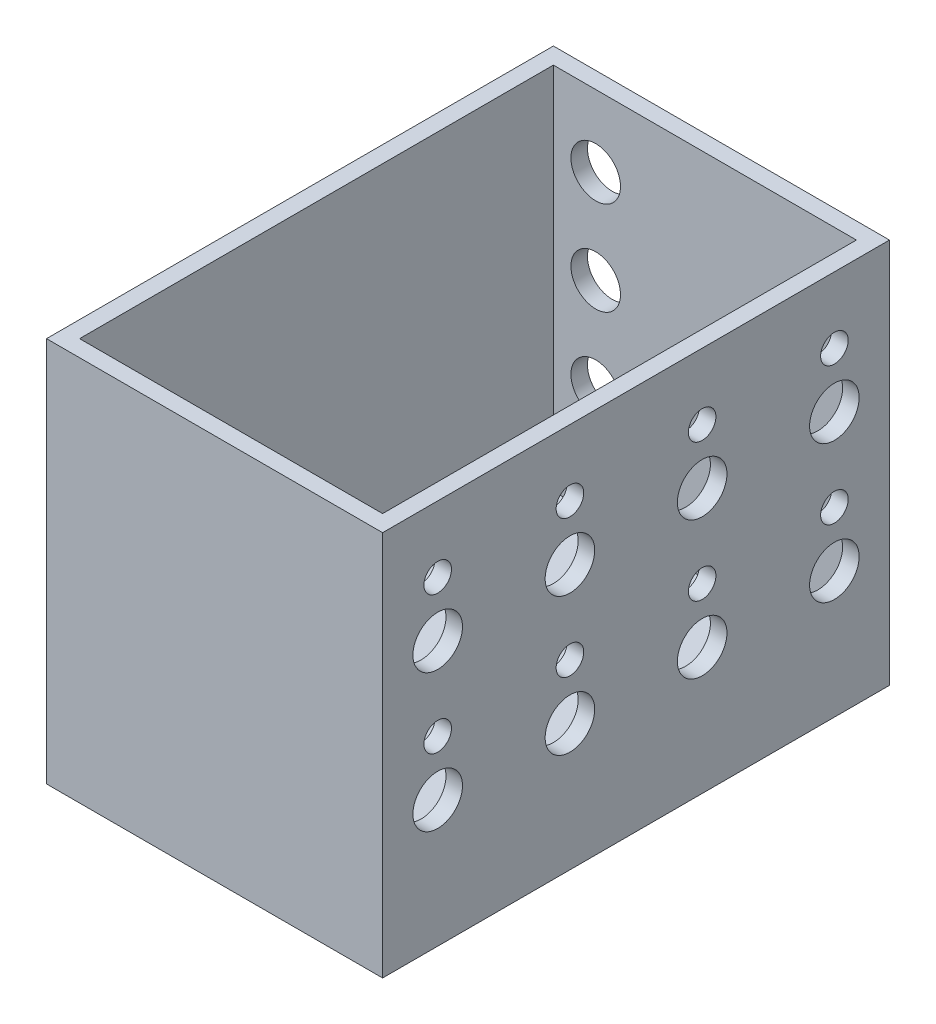
SolidWorks part; units mm, degrees
ref_plane "Front Plane" through (0, 0, 0) normal (0, 0, 1) x (1, 0, 0)
ref_plane "Top Plane" through (0, 0, 0) normal (0, 1, 0) x (1, 0, 0)
ref_plane "Right Plane" through (0, 0, 0) normal (1, 0, 0) x (0, 0, -1)
sketch "Sketch1" plane through (0, 0, 0) normal (0, 1, 0) x (1, 0, 0)
  line L1 (-27.5, -43) -> (27.5, -43)
  line L2 (-27.5, -43) -> (-27.5, 43)
  line L3 (-27.5, 43) -> (27.5, 43)
  line L4 (27.5, -43) -> (27.5, 43)
  line L5 (-27.5, -43) -> (27.5, 43) construction
  line L6 (-27.5, 43) -> (27.5, -43) construction
  point P0 (0, 0)
  dimension "D1" = 86
  dimension "D2" = 55
extrude "Boss-Extrude1" add sketch "Sketch1" along normal blind 3
sketch "Sketch2" plane through (0, 3, 0) normal (0, 1, 0) x (1, 0, 0)
  line L1 (-22.5, -22.5) -> (22.5, -22.5)
  line L2 (-22.5, -22.5) -> (-22.5, 22.5)
  line L3 (-22.5, 22.5) -> (22.5, 22.5)
  line L4 (22.5, -22.5) -> (22.5, 22.5)
  line L5 (-22.5, -22.5) -> (22.5, 22.5) construction
  line L6 (-22.5, 22.5) -> (22.5, -22.5) construction
  point P0 (0, 0)
  dimension "D1" = 45
  dimension "D2" = 45
extrude "Cut-Extrude1" cut sketch "Sketch2" against normal blind 1.5
sketch "Sketch3" plane through (0, 0, 0) normal (0, 1, 0) x (1, 0, 0)
  line L0 (-27.5, 43) -> (-27.5, -43)
  line L1 (-27.5, -43) -> (27.5, -43)
  line L2 (27.5, -43) -> (27.5, 43)
  line L3 (27.5, 43) -> (-27.5, 43)
  line L4 (-27.5, 43) -> (-27.5, 46) construction
  line L5 (27.5, 43) -> (27.5, 46) construction
  line L6 (27.5, -43) -> (27.5, -46) construction
  line L7 (-27.5, -43) -> (-27.5, -46) construction
  line L8 (-27.5, -43) -> (-30.5, -43) construction
  line L9 (-27.5, 43) -> (-30.5, 43) construction
  line L10 (27.5, 43) -> (30.5, 43) construction
  line L11 (27.5, -43) -> (30.5, -43) construction
  line L12 (-30.5, 43) -> (-30.5, 46) construction
  line L13 (-30.5, 46) -> (-30.5, -46)
  line L14 (-30.5, -46) -> (30.5, -46)
  line L15 (30.5, -46) -> (30.5, 46)
  line L16 (30.5, 46) -> (-30.5, 46)
  dimension "D1" = 3
  dimension "D2" = 3
extrude "Boss-Extrude2" add sketch "Sketch3" along normal blind 70
sketch "Sketch4" plane through (30.5, 0, 0) normal (1, 0, 0) x (0, 0, -1)
  line L0 (0, 0) -> (0, 23) construction
  line L1 (0, 23) -> (0, 48) construction
  line L2 (0, 23) -> (-12, 23) construction
  line L3 (0, 23) -> (12, 23) construction
  line L4 (0, 48) -> (-12, 48) construction
  line L5 (0, 48) -> (12, 48) construction
  line L6 (-12, 48) -> (-36, 48) construction
  line L7 (-12, 23) -> (-36, 23) construction
  line L8 (12, 48) -> (36, 48) construction
  line L9 (12, 23) -> (36, 23) construction
  line L10 (-36, 23) -> (-36, 33) construction
  line L11 (-12, 23) -> (-12, 33) construction
  line L12 (12, 23) -> (12, 33) construction
  line L13 (36, 23) -> (36, 33) construction
  line L14 (36, 48) -> (36, 58) construction
  line L15 (12, 48) -> (12, 58) construction
  line L16 (-12, 48) -> (-12, 58) construction
  line L17 (-36, 48) -> (-36, 58) construction
  circle A0 centre (-36, 48) radius 4.5
  circle A1 centre (-12, 48) radius 4.5
  circle A2 centre (12, 48) radius 4.5
  circle A3 centre (36, 48) radius 4.5
  circle A4 centre (36, 23) radius 4.5
  circle A5 centre (12, 23) radius 4.5
  circle A6 centre (-12, 23) radius 4.5
  circle A7 centre (-36, 23) radius 4.5
  circle A8 centre (-36, 33) radius 2.5
  circle A9 centre (-12, 33) radius 2.5
  circle A10 centre (12, 33) radius 2.5
  circle A11 centre (36, 33) radius 2.5
  circle A12 centre (36, 58) radius 2.5
  circle A13 centre (12, 58) radius 2.5
  circle A14 centre (-12, 58) radius 2.5
  circle A15 centre (-36, 58) radius 2.5
  dimension "D5" = 9
  dimension "D6" = 5
  dimension "D1" = 25
  dimension "D2" = 23
  dimension "D3" = 12
  dimension "D4" = 24
  dimension "D7" = 10
extrude "Cut-Extrude2" cut sketch "Sketch4" against normal blind 3
sketch "Sketch5" plane through (0, 0, -46) normal (0, 0, -1) x (-1, 0, 0)
  line L0 (0, 0) -> (0, 23) construction
  line L1 (19.8186, 23) -> (19.8186, 40) construction
  line L2 (0, 23) -> (19.8186, 23) construction
  line L3 (19.8186, 40) -> (19.8186, 57) construction
  circle A2 centre (19.8186, 23) radius 4.5
  circle A3 centre (19.8186, 40) radius 4.5
  circle A4 centre (19.8186, 57) radius 4.5
  dimension "D2" = 17
  dimension "D3" = 9
  dimension "D1" = 23
extrude "Cut-Extrude3" cut sketch "Sketch5" against normal blind 3
